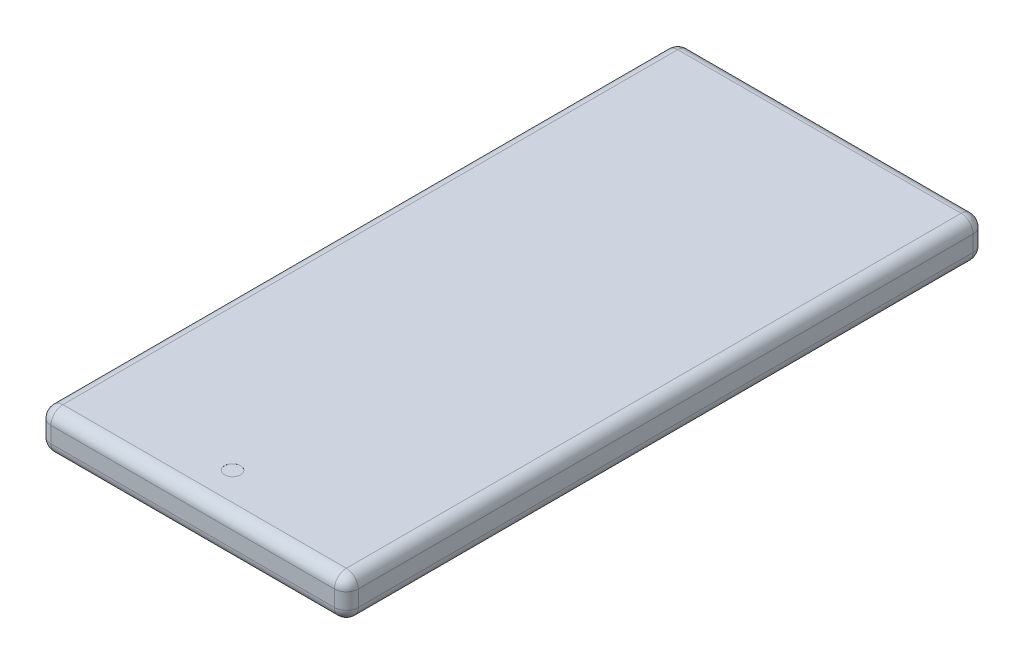
SolidWorks part; units mm, degrees
ref_plane "Front Plane" through (0, 0, 0) normal (0, 0, 1) x (1, 0, 0)
ref_plane "Top Plane" through (0, 0, 0) normal (0, 1, 0) x (1, 0, 0)
ref_plane "Right Plane" through (0, 0, 0) normal (1, 0, 0) x (0, 0, -1)
sketch "Sketch1" plane through (0, 0, 0) normal (0, 1, 0) x (1, 0, 0)
  line L1 (-38.5, 80) -> (38.5, 80)
  line L2 (-38.5, 80) -> (-38.5, -80)
  line L3 (-38.5, -80) -> (38.5, -80)
  line L4 (38.5, 80) -> (38.5, -80)
  line L5 (-38.5, 80) -> (38.5, -80) construction
  line L6 (-38.5, -80) -> (38.5, 80) construction
  point P0 (0, 0)
  dimension "D1" = 77
  dimension "D2" = 160
extrude "Boss-Extrude1" add sketch "Sketch1" along normal blind 10
fillet "Fillet1" radius 3 12 edges at (38.5, 0, 0) (0, 0, 80) (38.5, 10, 0) (0, 10, -80) (-38.5, 10, 0) (0, 10, 80) (38.5, 5, 80) (-38.5, 5, 80) (38.5, 5, -80) (-38.5, 0, 0) (-38.5, 5, -80) (0, 0, -80)
sketch "Sketch2" plane through (0, 10, 0) normal (0, 1, 0) x (1, 0, 0)
  line L1 (35.5, 77) -> (-35.5, 77) construction
  line L2 (35.5, -80) -> (-35.5, -80) construction
  circle A0 centre (0, -70) radius 2
  point P7 (0, 77)
  dimension "D2" = 4
  dimension "D1" = 10
extrude "Cut-Extrude1" cut sketch "Sketch2" against normal blind 0.01
sketch "Sketch3" plane through (0, 0, 0) normal (0, -1, 0) x (1, 0, 0)
  line L0 (-35.5, 80) -> (35.5, 80) construction
  line L1 (-28.5, 72) -> (-10.5, 72)
  line L2 (-32.5, 68) -> (-32.5, 34)
  line L3 (-28.5, 30) -> (-10.5, 30)
  line L4 (-6.5, 68) -> (-6.5, 34)
  line L5 (-38.5, -77) -> (-38.5, 77) construction
  arc A0 (-32.5, 34) -> (-28.5, 30) centre (-28.5, 34) ccw
  arc A1 (-10.5, 30) -> (-6.5, 34) centre (-10.5, 34) ccw
  arc A2 (-10.5, 72) -> (-6.5, 68) centre (-10.5, 68) cw
  arc A3 (-28.5, 72) -> (-32.5, 68) centre (-28.5, 68) ccw
  point P10 (-32.5, 30)
  point P13 (-6.5, 30)
  point P16 (-6.5, 72)
  dimension "D5" = 4
  dimension "D1" = 8
  dimension "D2" = 6
  dimension "D3" = 42
  dimension "D4" = 26
extrude "Boss-Extrude2" add sketch "Sketch3" along normal blind 2
fillet "Fillet2" radius 1 8 edges at (-7.6716, 0, 31.1716) (-19.5, 0, 30) (-31.3284, 0, 31.1716) (-32.5, 0, 51) (-31.3284, 0, 70.8284) (-19.5, 0, 72) (-7.6716, 0, 70.8284) (-6.5, 0, 51)
sketch "Sketch4" plane through (0, -2, 0) normal (0, -1, 0) x (1, 0, 0)
  line L0 (-32.5, 68) -> (-32.5, 34) construction
  line L1 (-6.5, 34) -> (-6.5, 68) construction
  line L2 (-25.25, 63.5) -> (-25.25, 51) construction
  line L3 (-25.25, 51) -> (-25.25, 38.5) construction
  circle A0 centre (-25.25, 63.5) radius 5.25
  circle A1 centre (-25.25, 51) radius 5.25
  circle A2 centre (-25.25, 38.5) radius 5.25
  circle A3 centre (-12, 57.25) radius 3.5
  circle A4 centre (-12, 44.75) radius 3.5
  point P10 (-25.25, 57.25)
  point P13 (-32.5, 51)
  point P14 (-25.25, 44.75)
  dimension "D1" = 10.5
  dimension "D5" = 7
  dimension "D2" = 7.25
  dimension "D3" = 12.5
  dimension "D4" = 12.5
  dimension "D6" = 5.5
extrude "Cut-Extrude2" cut sketch "Sketch4" against normal blind 1
sketch "Sketch5" plane through (0, -1, 0) normal (0, -1, 0) x (1, 0, 0)
  circle A0 centre (-12, 44.75) radius 2
  dimension "D1" = 4
extrude "Cut-Extrude3" cut sketch "Sketch5" against normal blind 0.01
